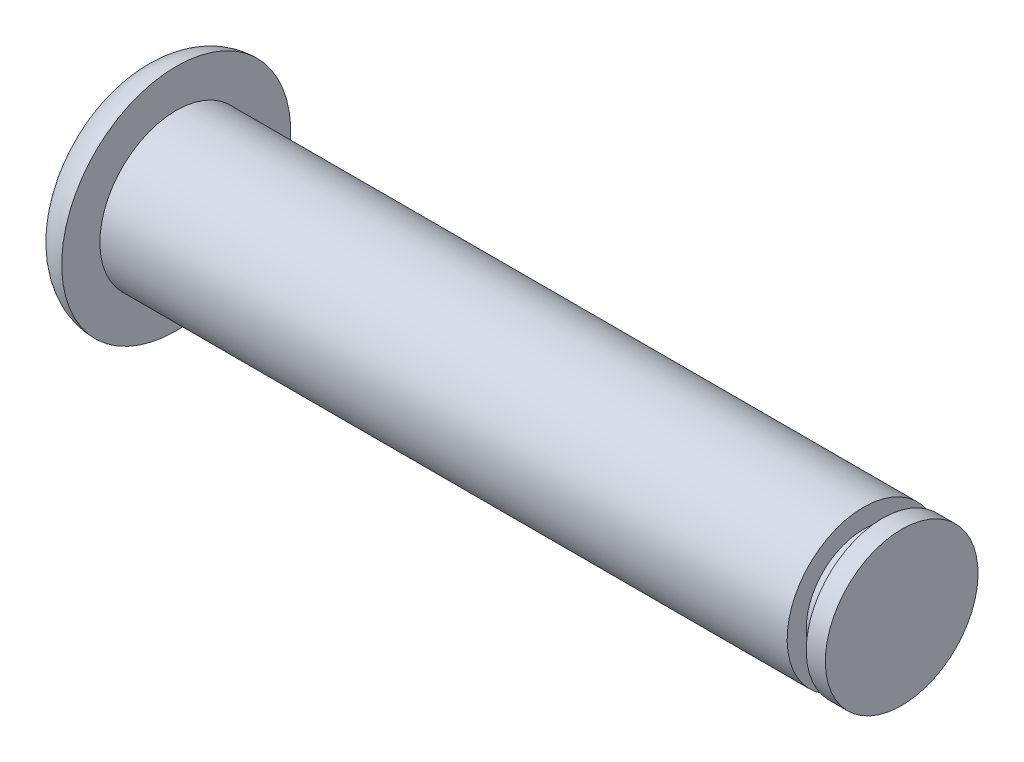
SolidWorks part; units mm, degrees
material "AISI 304"
ref_plane "Front Plane" through (0, 0, 0) normal (0, 0, 1) x (1, 0, 0)
ref_plane "Top Plane" through (0, 0, 0) normal (0, 1, 0) x (1, 0, 0)
ref_plane "Right Plane" through (0, 0, 0) normal (1, 0, 0) x (0, 0, -1)
sketch "Sketch1" plane through (0, 0, 0) normal (0, 0, -1) x (-1, 0, 0)
  line L0 (0, 0) -> (0, 2)
  line L1 (0, 2) -> (0.5, 2)
  line L2 (20, 2) -> (20, 0)
  line L3 (20, 0) -> (0, 0)
  line L4 (19, 2) -> (19, 3)
  line L5 (1, 2) -> (1, 1.5)
  line L6 (1, 1.5) -> (0.5, 1.5)
  line L7 (0.5, 1.5) -> (0.5, 2)
  line L8 (1, 2) -> (19, 2)
  line L9 (0, 0) -> (25.1757, 0) construction
  arc A0 (20, 2) -> (19, 3) centre (19, 2) ccw
  point P4 (19, 2)
  point P9 (1, 2)
  dimension "D1" = 2
  dimension "D2" = 20
  dimension "D3" = 1
  dimension "D4" = 1
  dimension "D5" = 1
  dimension "D6" = 0.5
  dimension "D7" = 0.5
revolve "Revolve1" add sketch "Sketch1" angle 360 about L9
